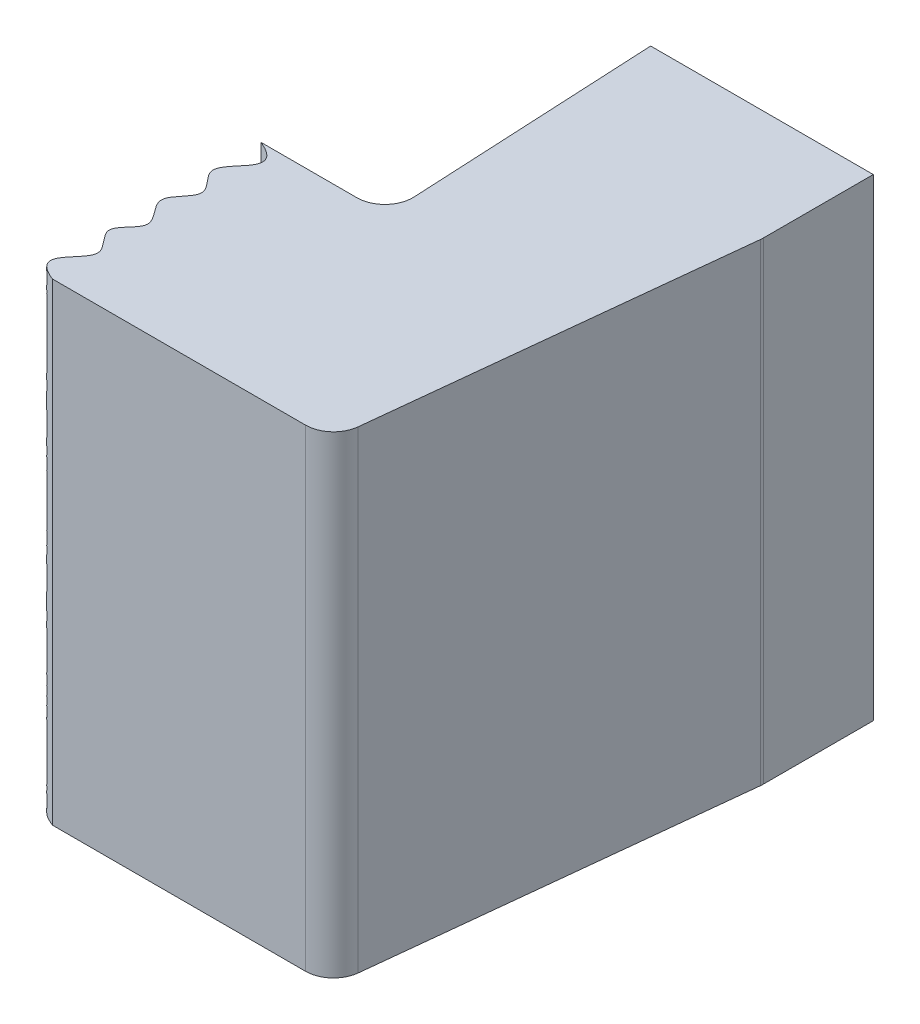
SolidWorks part; units mm, degrees
ref_plane "Front Plane" through (0, 0, 0) normal (0, 0, 1) x (1, 0, 0)
ref_plane "Top Plane" through (0, 0, 0) normal (0, 1, 0) x (1, 0, 0)
ref_plane "Right Plane" through (0, 0, 0) normal (1, 0, 0) x (0, 0, -1)
sketch "Sketch1" plane through (0, 0, 0) normal (0, 1, 0) x (1, 0, 0)
  line L0 (0, 0) -> (8, 0)
  line L1 (8, 0) -> (8, -4)
  line L2 (8, -4) -> (6.5, -18)
  line L3 (6.5, -18) -> (-3.5, -18)
  line L5 (-3.5, -10) -> (0.5, -10)
  line L6 (0.5, -10) -> (0, 0)
  line L7 (-3.5, -10) -> (-4, -10)
  spline S0 degree 3 poles (-4, -10) (-2.5201, -10.6065) (-4.8664, -11.474) (-3.0323, -12.6462) (-4.5278, -13.5842) (-2.9917, -14.5771) (-4.4607, -15.4466) (-2.6389, -16.6074) (-4.9081, -17.4384) (-3.5, -18) knots 0 0 0 0 0.221862 0.329574 0.444854 0.572312 0.676833 0.787769 1 1 1 1
  dimension "D2" = 4
  dimension "D8" = 0.5
  dimension "D1" = 8
  dimension "D3" = 10
  dimension "D4" = 8
  dimension "D5" = 4
  dimension "D6" = 18
  dimension "D7" = 1.5
extrude "Boss-Extrude1" add sketch "Sketch1" along normal blind 17
fillet "Fillet1" radius 1 3 edges at (8, 8.5, 4) (0.5, 8.5, 10) (6.5, 8.5, 18)
